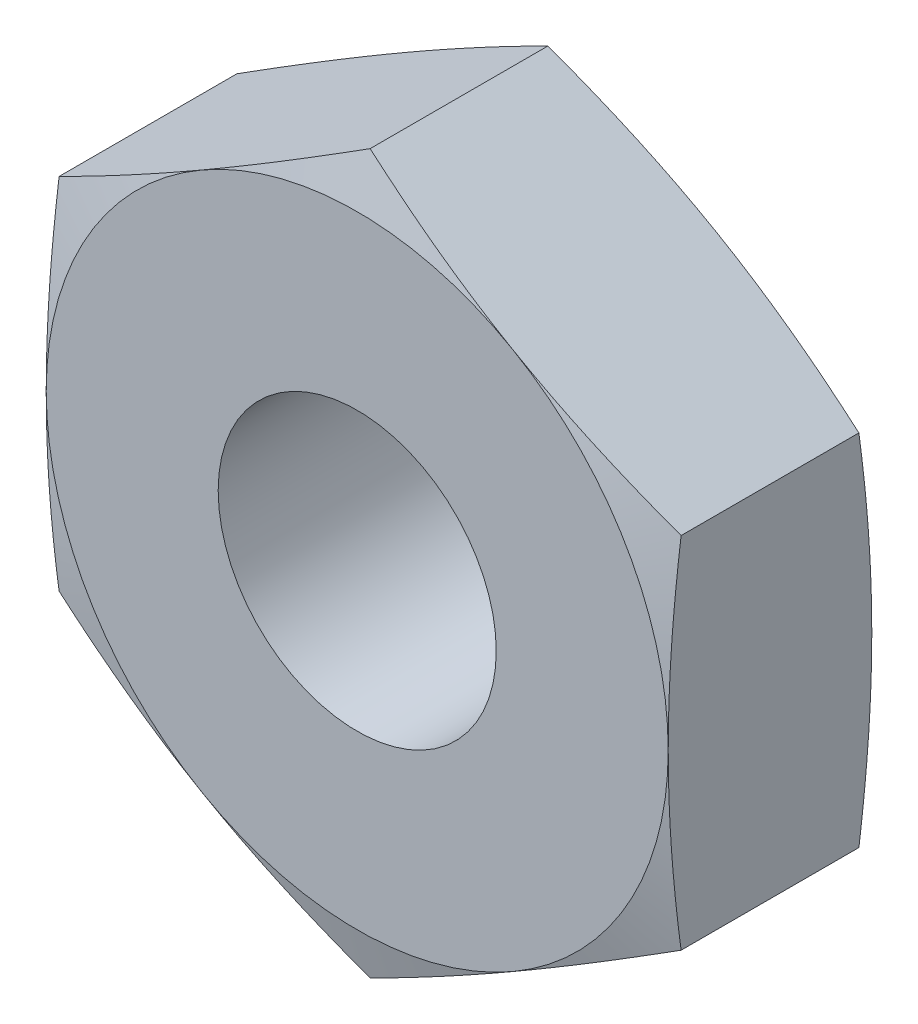
SolidWorks part; units mm, degrees
ref_plane "基准面1" through (0, 0, 0) normal (0, 0, 1) x (1, 0, 0)
ref_plane "基准面2" through (0, 0, 0) normal (0, 1, 0) x (1, 0, 0)
ref_plane "基准面3" through (0, 0, 0) normal (1, 0, 0) x (0, 0, -1)
sketch "尺寸草图" plane through (0, 0, 0) normal (0, 0, 1) x (1, 0, 0)
  line L0 (0, 0) -> (5.88, 0) construction
  line L3 (-2.8571, 0) -> (0, 0) construction
  point P0 (-2.3571, 0)
  point P3 (3, 0)
  point P4 (0, 0)
  point P5 (5.88, 0)
  point P6 (1.8, 0)
  point P8 (5.5, 0)
  dimension "D1" = 2.8571
  dimension "D" = 3
  dimension "P" = 0.5
  dimension "e(min)" = 5.88
  dimension "m(max)" = 1.8
  dimension "s(max)" = 5.5
sketch "草图1" plane through (0, 0, 0) normal (0, 0, 1) x (1, 0, 0)
  line L0 (-2.75, 0) -> (2.75, 0) construction
  line L1 (0, 3.1754) -> (0, -3.1754) construction
  line L3 (0, 3.1754) -> (-2.75, 1.5877)
  line L4 (-2.75, 1.5877) -> (-2.75, -1.5877)
  line L5 (-2.75, -1.5877) -> (0, -3.1754)
  line L6 (0, -3.1754) -> (2.75, -1.5877)
  line L7 (2.75, -1.5877) -> (2.75, 1.5877)
  line L8 (2.75, 1.5877) -> (0, 3.1754)
  circle A0 centre (0, 0) radius 2.75 construction
  circle A1 centre (0, 0) radius 1.2294
  dimension "D1" = 5.5
  dimension "D" = 2.4588
extrude "基体-拉伸" add sketch "草图1" along normal blind 1.8
cosmetic thread "装饰螺纹线1" parameters "D2"=3
sketch "草图2" plane through (0, 0, 0) normal (0, 0, -1) x (-1, 0, 0)
  circle A0 centre (0, 0) radius 2.75
  circle A1 centre (0, 0) radius 1.2294 construction
  dimension "s" = 5.5
extrude "切除-拉伸1" cut sketch "草图2" against normal through all draft 75 flip side to cut
sketch "草图3" plane through (0, 0, 1.8) normal (0, 0, 1) x (1, 0, 0)
  circle A0 centre (0, 0) radius 2.75
  dimension "D1" = 5.5
extrude "切除-拉伸2" cut sketch "草图3" against normal through all draft 75 flip side to cut
